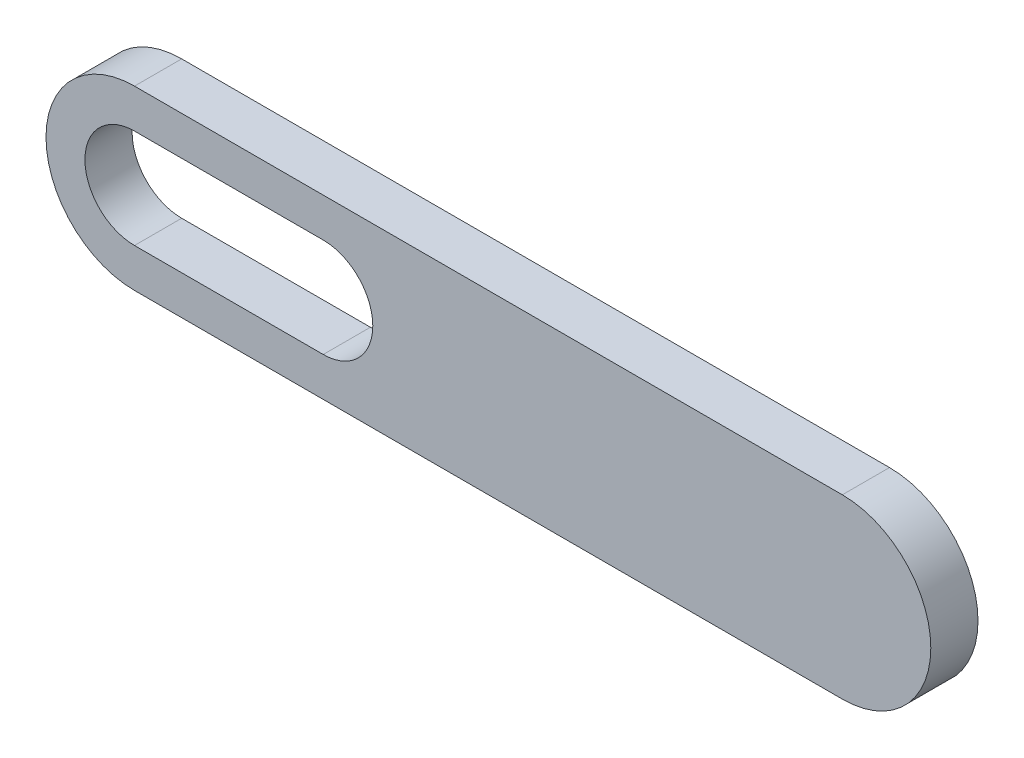
SolidWorks part; units mm, degrees
ref_plane "Front" through (0, 0, 0) normal (0, 0, 1) x (1, 0, 0)
ref_plane "Top" through (0, 0, 0) normal (0, 1, 0) x (1, 0, 0)
ref_plane "Right" through (0, 0, 0) normal (1, 0, 0) x (0, 0, -1)
sketch "Sketch1" plane through (0, 0, 0) normal (0, 0, 1) x (1, 0, 0)
  line L0 (-40, 21) -> (40, -21) construction
  line L1 (-40, 37.5) -> (260, 37.5)
  line L2 (-40, 0) -> (260, 0) construction
  line L3 (-40, -37.5) -> (260, -37.5)
  line L4 (50, 0) -> (-50, 0) construction
  line L5 (-40, 21) -> (40, 21)
  line L7 (-40, -21) -> (40, -21)
  arc A0 (-40, 37.5) -> (-40, -37.5) centre (-40, 0) ccw
  arc A1 (260, 37.5) -> (260, -37.5) centre (260, 0) cw
  arc A2 (-40, 21) -> (-40, -21) centre (-40, 0) ccw
  arc A3 (40, 21) -> (40, -21) centre (40, 0) cw
  dimension "D1" = 75
  dimension "D2" = 42
  dimension "D3" = 80
  dimension "D4" = 300
extrude "Extrude1" add sketch "Sketch1" along normal blind 20
